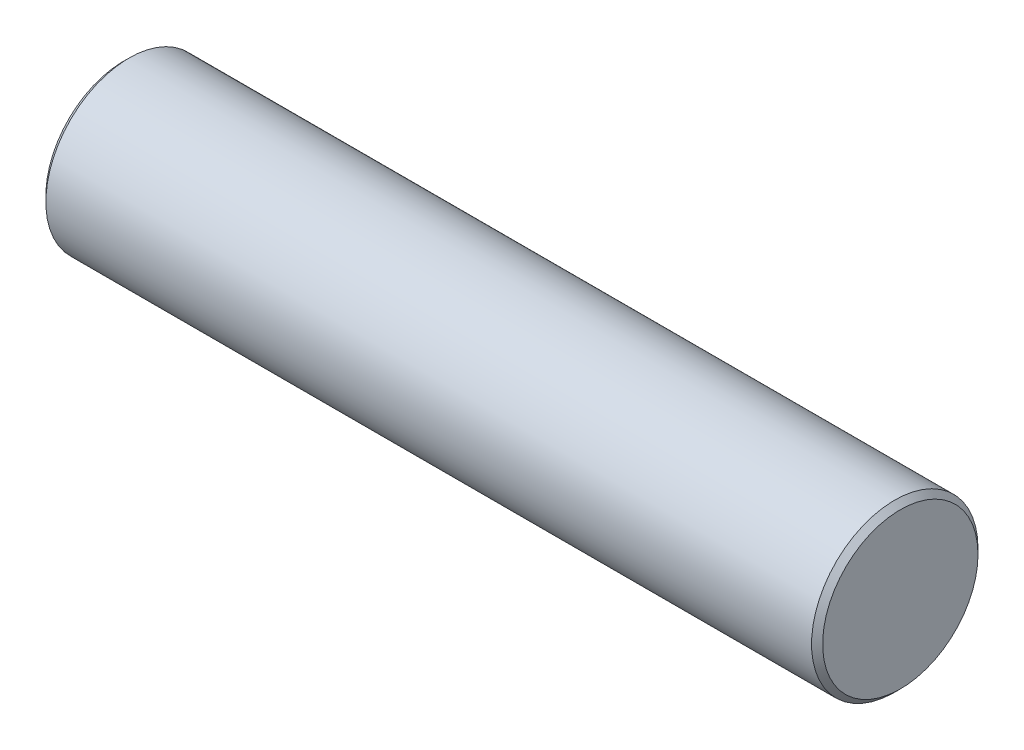
SolidWorks part; units mm, degrees
ref_plane "Front Plane" through (0, 0, 0) normal (0, 0, 1) x (1, 0, 0)
ref_plane "Top Plane" through (0, 0, 0) normal (0, 1, 0) x (1, 0, 0)
ref_plane "Right Plane" through (0, 0, 0) normal (1, 0, 0) x (0, 0, -1)
sketch "Sketch1" plane through (0, 0, 0) normal (1, 0, 0) x (0, 0, -1)
  circle A0 centre (0, 0) radius 1.5
  dimension "D1" = 3
extrude "Boss-Extrude1" add sketch "Sketch1" along normal blind 14
chamfer "Chamfer1" distance 0.1 angle 45 2 edges at (0, 0, -1.5) (14, 0, -1.5)
